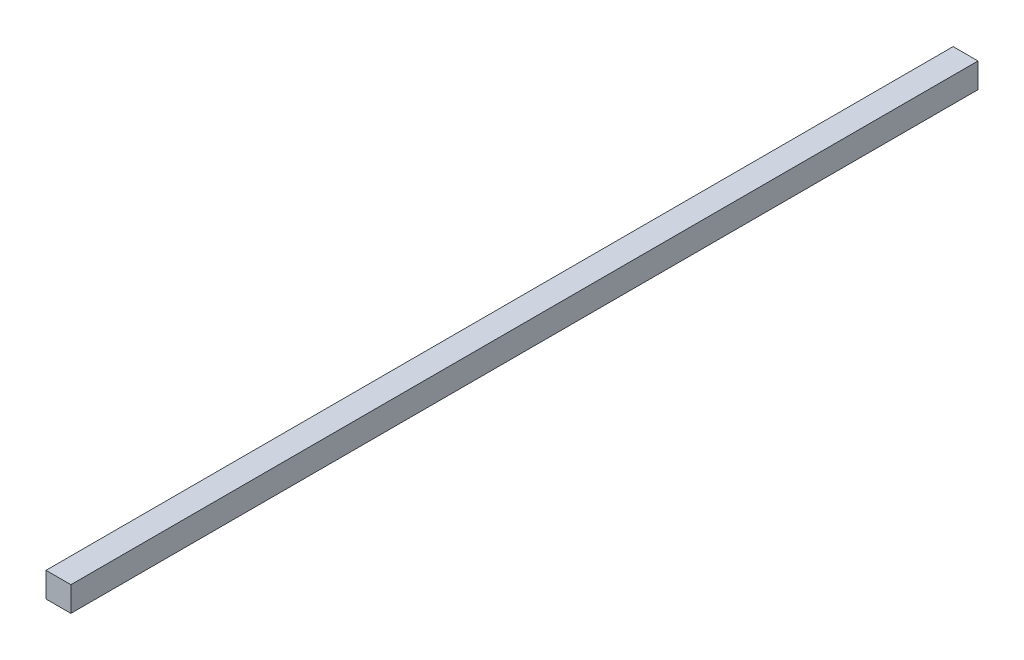
SolidWorks part; units mm, degrees
ref_plane "Front Plane" through (0, 0, 0) normal (0, 0, 1) x (1, 0, 0)
ref_plane "Top Plane" through (0, 0, 0) normal (0, 1, 0) x (1, 0, 0)
ref_plane "Right Plane" through (0, 0, 0) normal (1, 0, 0) x (0, 0, -1)
sketch "Sketch1" plane through (0, 0, 0) normal (0, 0, 1) x (1, 0, 0)
  line L1 (-5, 5) -> (5, 5)
  line L2 (-5, 5) -> (-5, -5)
  line L3 (-5, -5) -> (5, -5)
  line L4 (5, 5) -> (5, -5)
  line L5 (-5, 5) -> (5, -5) construction
  line L6 (-5, -5) -> (5, 5) construction
  point P0 (0, 0)
  dimension "D1" = 10
  dimension "D2" = 10
extrude "Boss-Extrude1" add sketch "Sketch1" along normal blind 364.6
